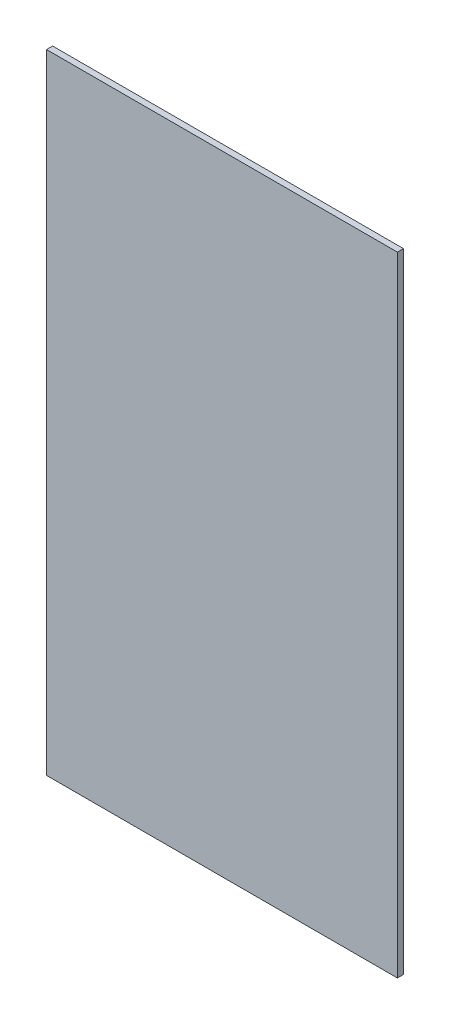
SolidWorks part; units mm, degrees
material "6061-T6 (SS)"
ref_plane "Front Plane" through (0, 0, 0) normal (1, 0, 0) x (0, 1, 0)
ref_plane "Top Plane" through (0, 0, 0) normal (0, 0, 1) x (0, 1, 0)
ref_plane "Right Plane" through (0, 0, 0) normal (0, 1, 0) x (-1, 0, 0)
sketch "Sketch1" plane through (0, 0, 0) normal (0, 0, 1) x (0, 1, 0)
  line L1 (-103, -57.5) -> (103, -57.5)
  line L2 (-103, -57.5) -> (-103, 57.5)
  line L3 (-103, 57.5) -> (103, 57.5)
  line L4 (103, -57.5) -> (103, 57.5)
  line L5 (-103, -57.5) -> (103, 57.5) construction
  line L6 (-103, 57.5) -> (103, -57.5) construction
  point P0 (0, 0)
  dimension "D1" = 115
  dimension "D2" = 206
extrude "Boss-Extrude1" add sketch "Sketch1" along normal blind 2
